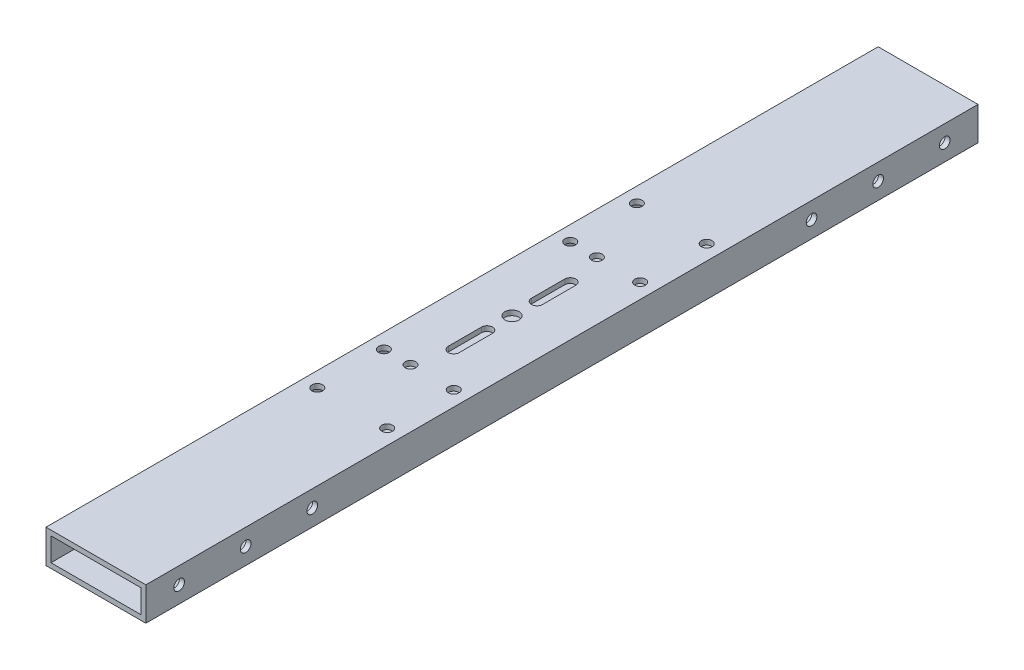
SolidWorks part; units mm, degrees
material "6061 合金"
ref_plane "前视基准面" through (0, 0, 0) normal (0, 0, 1) x (1, 0, 0)
ref_plane "上视基准面" through (0, 0, 0) normal (0, 1, 0) x (1, 0, 0)
ref_plane "右视基准面" through (0, 0, 0) normal (1, 0, 0) x (0, 0, -1)
other "Configuration Table"
sketch "草图1" plane through (0, 0, 0) normal (0, 0, 1) x (1, 0, 0)
  line L1 (-15, 5) -> (15, 5)
  line L2 (-15, 5) -> (-15, -5)
  line L3 (-15, -5) -> (15, -5)
  line L4 (15, 5) -> (15, -5)
  line L5 (-15, 5) -> (15, -5) construction
  line L6 (-15, -5) -> (15, 5) construction
  line L7 (-13.5, 3.5) -> (13.5, 3.5)
  line L8 (-13.5, 3.5) -> (-13.5, -3.5)
  line L9 (-13.5, -3.5) -> (13.5, -3.5)
  line L10 (13.5, 3.5) -> (13.5, -3.5)
  line L11 (-13.5, 3.5) -> (13.5, -3.5) construction
  line L12 (-13.5, -3.5) -> (13.5, 3.5) construction
  point P0 (0, 0)
  point P6 (0, 0)
  dimension "D1" = 1.5
  dimension "D2" = 1.5
  dimension "D3" = 10
  dimension "D4" = 30
extrude "凸台-拉伸1" add sketch "草图1" along normal blind 250
sketch "草图2" plane through (15, 0, 0) normal (1, 0, 0) x (0, 0, -1)
  line L0 (0, 0) -> (-281.3553, 0) construction
  line L1 (-250, -5) -> (-250, 5) construction
  line L2 (-240, 0) -> (-220, 0) construction
  line L3 (-125, 5) -> (-125, 97.1982) construction
  line L4 (-250, 5) -> (0, 5) construction
  circle A0 centre (-240, 0) radius 1.6
  circle A1 centre (-220, 0) radius 1.6
  circle A2 centre (-200, 0) radius 1.6
  circle A3 centre (-50, 0) radius 1.6
  circle A4 centre (-30, 0) radius 1.6
  circle A5 centre (-10, 0) radius 1.6
  dimension "D1" = 10
  dimension "D2" = 3.2
  dimension "D4" = 20
  dimension "D3" = 3
extrude "切除-拉伸1" cut sketch "草图2" against normal through all
sketch "草图3" plane through (0, 5, 0) normal (0, 1, 0) x (1, 0, 0)
  line L0 (4, 0) -> (4, -260.0948) construction
  line L1 (-15, -125) -> (203.3183, -125) construction
  line L2 (-15, -250) -> (-15, 0) construction
  line L3 (15, 0) -> (-15, 0) construction
  circle A0 centre (-2.5, -97) radius 1.6
  circle A1 centre (10.5, -97) radius 1.6
  circle A2 centre (-2.5, -153) radius 1.6
  circle A3 centre (10.5, -153) radius 1.6
  circle A4 centre (-2.5, -125) radius 1.6 construction
  circle A5 centre (10.5, -125) radius 1.6 construction
  circle A6 centre (10.5, -173) radius 1.6
  circle A7 centre (10.5, -77) radius 1.6
  circle A8 centre (-10.5, -173) radius 1.6
  circle A9 centre (-10.5, -153) radius 1.6
  circle A10 centre (-10.5, -77) radius 1.6
  circle A11 centre (-10.5, -97) radius 1.6
  dimension "D1" = 3.2
  dimension "D3" = 56
  dimension "D2" = 13
  dimension "D5" = 20
  dimension "D6" = 21
  dimension "D4" = 4
extrude "切除-拉伸2" cut sketch "草图3" against normal through all
sketch "草图4" plane through (0, 5, 0) normal (0, 1, 0) x (1, 0, 0)
  line L2 (-1.65, -107.5) -> (-1.65, -117.5)
  line L3 (1.65, -117.5) -> (1.65, -107.5)
  line L4 (-1.65, -107.5) -> (-1.65, -117.5)
  line L5 (1.65, -117.5) -> (1.65, -107.5)
  line L6 (1.65, -142.5) -> (1.65, -132.5)
  line L7 (-1.65, -132.5) -> (-1.65, -142.5)
  line L8 (1.65, -142.5) -> (1.65, -132.5)
  line L9 (-1.65, -132.5) -> (-1.65, -142.5)
  circle A1 centre (0, -125) radius 2.15
  circle A2 centre (0, -125) radius 2.15
  arc A4 (-1.65, -117.5) -> (1.65, -117.5) centre (0, -117.5) ccw
  arc A5 (1.65, -107.5) -> (-1.65, -107.5) centre (0, -107.5) ccw
  arc A6 (-1.65, -117.5) -> (1.65, -117.5) centre (0, -117.5) ccw
  arc A7 (1.65, -107.5) -> (-1.65, -107.5) centre (0, -107.5) ccw
  arc A8 (1.65, -132.5) -> (-1.65, -132.5) centre (0, -132.5) ccw
  arc A9 (-1.65, -142.5) -> (1.65, -142.5) centre (0, -142.5) ccw
  arc A10 (1.65, -132.5) -> (-1.65, -132.5) centre (0, -132.5) ccw
  arc A11 (-1.65, -142.5) -> (1.65, -142.5) centre (0, -142.5) ccw
  dimension "D1" = 0
  dimension "D2" = 0
  dimension "D3" = 0
extrude "切除-拉伸3" cut sketch "草图4" against normal through all
sketch "草图5" plane through (0, 5, 0) normal (0, 1, 0) x (1, 0, 0)
  line L0 (0, -15) -> (0, -65) construction
  line L1 (9, -15) -> (9, -65)
  line L2 (-9, -15) -> (-9, -65)
  line L3 (15, -250) -> (15, 0) construction
  line L4 (15, -125) -> (-58.6377, -125) construction
  line L5 (0, -235) -> (0, -185) construction
  line L6 (9, -235) -> (9, -185)
  line L7 (-9, -235) -> (-9, -185)
  arc A0 (9, -15) -> (-9, -15) centre (0, -15) ccw
  arc A1 (-9, -65) -> (9, -65) centre (0, -65) ccw
  arc A2 (9, -235) -> (-9, -235) centre (0, -235) cw
  arc A3 (-9, -185) -> (9, -185) centre (0, -185) cw
  point P2 (0, -40)
  point P14 (0, -210)
  dimension "D1" = 6
  dimension "D2" = 15
  dimension "D3" = 50
extrude "切除-拉伸4" [suppressed] cut sketch "草图5" against normal through all
